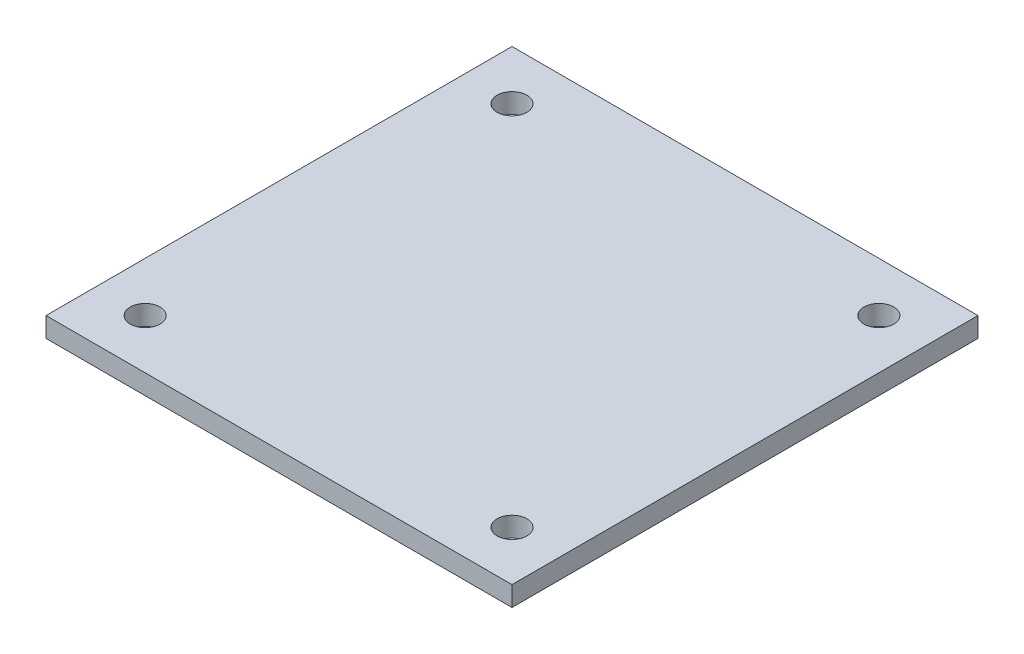
SolidWorks part; units mm, degrees
ref_plane "Ön Düzlem" through (0, 0, 0) normal (0, 0, 1) x (1, 0, 0)
ref_plane "Üst Düzlem" through (0, 0, 0) normal (0, 1, 0) x (1, 0, 0)
ref_plane "Sağ Düzlem" through (0, 0, 0) normal (1, 0, 0) x (0, 0, -1)
sketch "Çizim1" plane through (0, 0, 0) normal (0, 1, 0) x (1, 0, 0)
  line L1 (-117.5, 117.5) -> (117.5, 117.5)
  line L2 (-117.5, 117.5) -> (-117.5, -117.5)
  line L3 (-117.5, -117.5) -> (117.5, -117.5)
  line L4 (117.5, 117.5) -> (117.5, -117.5)
  point P4 (0, 117.5)
  point P6 (-117.5, 0)
  point P12 (0, -117.5)
  dimension "D1" = 235
  dimension "D2" = 235
extrude "Yükseklik-Ekstrüzyon1" add sketch "Çizim1" along normal blind 10
sketch "Çizim2" plane through (0, 10, 0) normal (0, 1, 0) x (1, 0, 0)
  line L0 (-117.5, 117.5) -> (-117.5, -117.5) construction
  line L2 (117.5, 117.5) -> (-117.5, 117.5) construction
  line L3 (-117.5, -117.5) -> (117.5, -117.5) construction
  line L4 (117.5, -117.5) -> (117.5, 117.5) construction
  circle A0 centre (-92.5, 92.5) radius 7.5
  circle A1 centre (-92.5, -92.5) radius 7.5
  circle A2 centre (92.5, -92.5) radius 7.5
  circle A3 centre (92.5, 92.5) radius 7.5
  point P8 (0, 0)
  point P9 (0, 0)
  point P10 (0, 0)
  point P11 (0, 0)
  point P12 (82.9292, -92.0021)
  point P15 (0, 0)
  point P18 (0, 0)
  dimension "D3" = 15
  dimension "D1" = 25
  dimension "D2" = 25
  dimension "D4" = 25
  dimension "D5" = 25
extrude "Kes-Ekstrüzyon1" cut sketch "Çizim2" against normal through all
